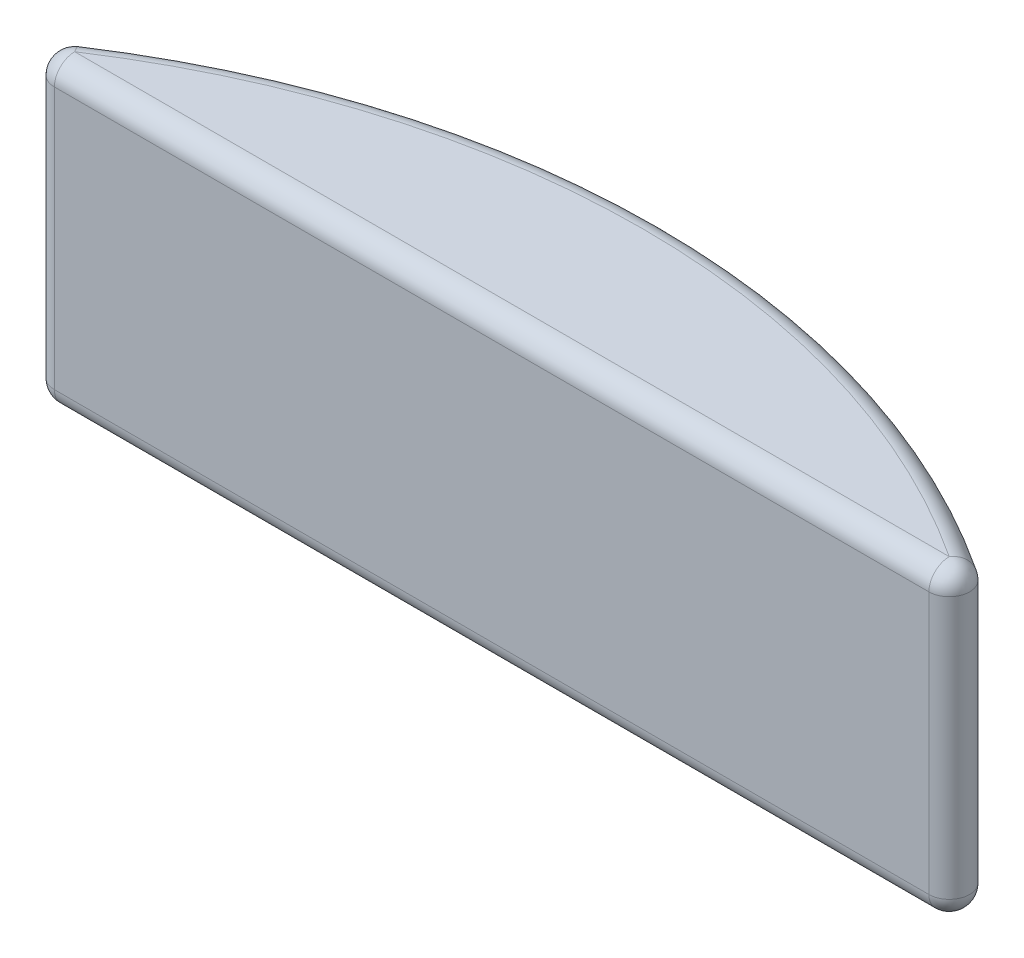
SolidWorks part; units mm, degrees
material "Pure Lead"
ref_plane "Front Plane" through (0, 0, 0) normal (0, 0, 1) x (1, 0, 0)
ref_plane "Top Plane" through (0, 0, 0) normal (0, 1, 0) x (1, 0, 0)
ref_plane "Right Plane" through (0, 0, 0) normal (1, 0, 0) x (0, 0, -1)
sketch "Sketch1" plane through (0, 0, 0) normal (0, 1, 0) x (1, 0, 0)
  line L0 (-34.4079, 50.8) -> (34.4079, 50.8)
  arc A0 (-35.2862, 53.7378) -> (35.2862, 53.7378) centre (0, 0) cw
  arc A1 (35.2862, 53.7378) -> (34.4079, 50.8) centre (34.4079, 52.4002) cw
  arc A2 (-35.2862, 53.7378) -> (-34.4079, 50.8) centre (-34.4079, 52.4002) ccw
  circle A3 centre (0, 0) radius 64.2874 construction
  point P9 (-25.3703, 50.4631)
  dimension "D1" = 1.6002
  dimension "D2" = 128.5748
  dimension "D3" = 50.8
extrude "Boss-Extrude1" add sketch "Sketch1" along normal blind 23.8252
fillet "Fillet1" radius 1.6002 8 edges at (0, 0, -64.2874) (-35.9411, 0, -51.9418) (0, 0, -50.8) (35.9411, 0, -51.9418) (0, 23.8252, -50.8) (-35.9411, 23.8252, -51.9418) (0, 23.8252, -64.2874) (35.9411, 23.8252, -51.9418)
